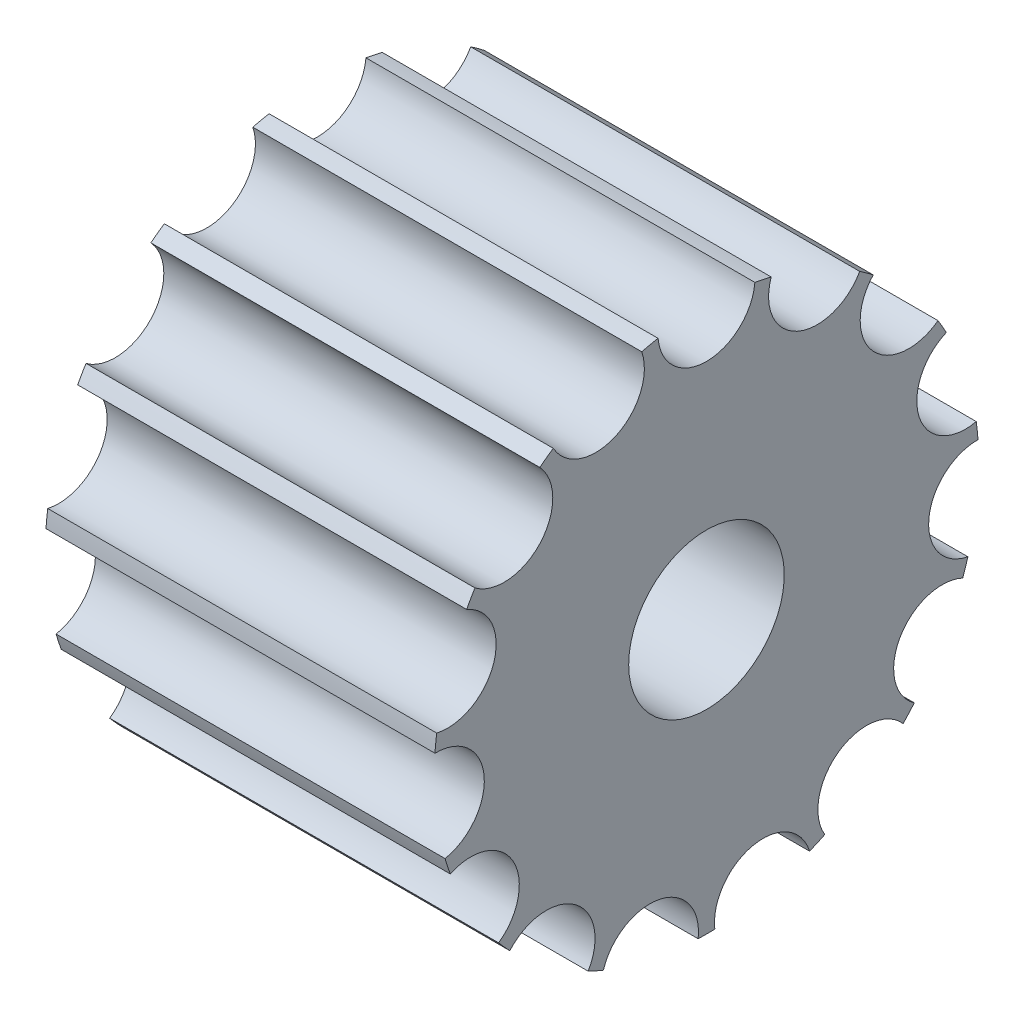
SolidWorks part; units mm, degrees
ref_plane "前视基准面" through (0, 0, 0) normal (0, 0, 1) x (1, 0, 0)
ref_plane "上视基准面" through (0, 0, 0) normal (0, 1, 0) x (1, 0, 0)
ref_plane "右视基准面" through (0, 0, 0) normal (1, 0, 0) x (0, 0, -1)
sketch "草图1" plane through (0, 0, 0) normal (0, 0, 1) x (1, 0, 0)
  line L0 (-27.3637, 8.8472) -> (-27.3637, 3.8472)
  line L1 (-27.3637, 3.8472) -> (-28.6137, 3.8472)
  line L2 (-28.6137, 3.8472) -> (-28.6137, 1.8472)
  line L3 (-17.3637, 8.8472) -> (-27.3637, 8.8472)
  line L4 (-48.9645, 1.8472) -> (-7.7326, 1.8472) construction
  line L6 (-28.6137, 1.8472) -> (-16.1137, 1.8472)
  line L8 (-17.3637, 8.8472) -> (-17.3637, 3.8472)
  line L9 (-16.1137, 3.8472) -> (-16.1137, 1.8472)
  line L10 (-17.3637, 3.8472) -> (-16.1137, 3.8472)
  dimension "D1" = 10
  dimension "D2" = 7
  dimension "D3" = 2
  dimension "D4" = 1.25
revolve "旋转2" add sketch "草图1" angle 360 about L4
sketch "草图3" plane through (-28.6137, 0, 0) normal (-1, 0, 0) x (0, 0, 1)
  circle A0 centre (0, 1.8472) radius 2
  dimension "D1" = 4
extrude "切除-拉伸2" cut sketch "草图3" against normal blind 17
sketch "草图4" plane through (-27.3637, 0, 0) normal (-1, 0, 0) x (0, 0, 1)
  line L1 (-1.25, 8.8472) -> (1.25, 8.8472)
  line L2 (-1.25, 8.8472) -> (-1.25, 11.5305)
  line L3 (-1.25, 11.5305) -> (1.25, 11.5305)
  line L4 (1.25, 8.8472) -> (1.25, 11.5305)
  arc A0 (-1.25, 8.8472) -> (1.25, 8.8472) centre (0, 8.8472) ccw
  circle A1 centre (0, 1.8472) radius 7 construction
  circle M7 centre (0, 1.8472) radius 7
  dimension "D1" = 2.5
extrude "切除-拉伸3" cut sketch "草图4" against normal blind 17 contours A0 M7
pattern_circular "阵列(圆周)1" count 15 over 360 about axis through (0, 1.8472, 0) along (1, 0, 0) of "切除-拉伸3"
